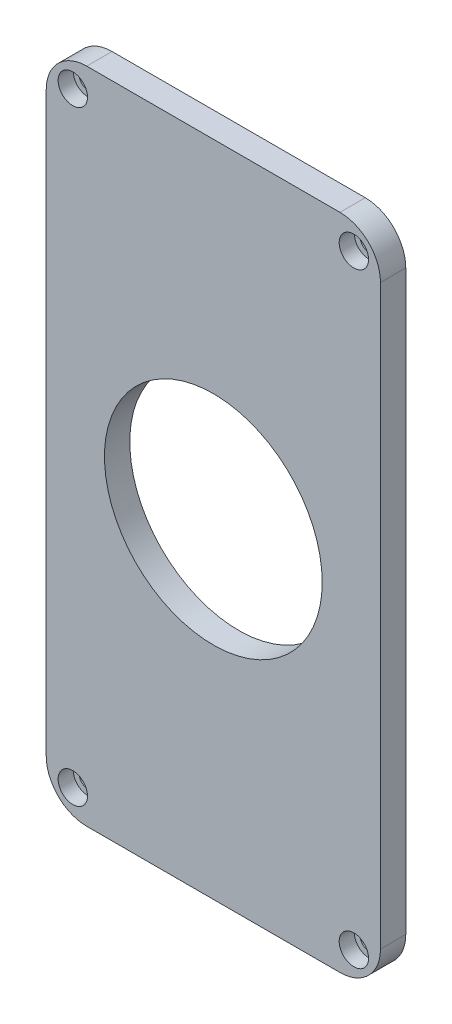
SolidWorks part; units mm, degrees
ref_plane "Front Plane" through (0, 0, 0) normal (0, 0, 1) x (1, 0, 0)
ref_plane "Top Plane" through (0, 0, 0) normal (0, 1, 0) x (1, 0, 0)
ref_plane "Right Plane" through (0, 0, 0) normal (1, 0, 0) x (0, 0, -1)
sketch "Sketch1" plane through (0, 0, 0) normal (0, 0, 1) x (1, 0, 0)
  line L5 (25, 65) -> (-25, 65)
  line L6 (33, 57) -> (33, -57)
  line L7 (25, -65) -> (-25, -65)
  line L8 (-33, 57) -> (-33, -57)
  line L9 (33, 65) -> (-33, -65) construction
  line L10 (33, -65) -> (-33, 65) construction
  arc A4 (-33, -57) -> (-25, -65) centre (-25, -57) ccw
  arc A5 (25, -65) -> (33, -57) centre (25, -57) ccw
  arc A6 (33, 57) -> (25, 65) centre (25, 57) ccw
  arc A7 (-33, 57) -> (-25, 65) centre (-25, 57) cw
  point P0 (0, 0)
  dimension "D1" = 130
  dimension "D2" = 8
  dimension "D3" = 50
extrude "Boss-Extrude1" add sketch "Sketch1" along normal blind 5
sketch "Sketch2" plane through (0, 0, 5) normal (0, 0, 1) x (1, 0, 0)
  circle A0 centre (0, 0) radius 21.5
  dimension "D1" = 43
extrude "Cut-Extrude1" cut sketch "Sketch2" against normal through all
sketch "Sketch12" plane through (0, 0, 5) normal (0, 0, 1) x (1, 0, 0)
  line L6 (0, 0) -> (0, 59.75) construction
  line L7 (0, 59.75) -> (-27.75, 59.75) construction
  line L8 (0, 0) -> (-27.75, 0) construction
  line L9 (-27.75, 0) -> (-27.75, 59.75) construction
  line L10 (-27.75, 59.75) -> (-30.6569, 59.446) construction
  circle A0 centre (-27.75, 59.75) radius 2.9
  circle A1 centre (27.75, 59.75) radius 2.9
  circle A2 centre (-27.75, -59.75) radius 2.9
  circle A3 centre (27.75, -59.75) radius 2.9
  circle A4 centre (-27.75, 59.75) radius 3 construction
  dimension "D3" = 5.8
  dimension "D4" = 6
  dimension "D1" = 27.75
  dimension "D2" = 59.75
extrude "Cut-Extrude3" cut sketch "Sketch12" against normal blind 3
sketch "Sketch13" plane through (0, 0, 2) normal (0, 0, 1) x (1, 0, 0)
  line L0 (0, 0) -> (0, 65) construction
  line L1 (25, 65) -> (-25, 65) construction
  line L2 (0, 0) -> (-27.75, 0) construction
  circle A0 centre (-27.75, 59.75) radius 1.75
  circle A1 centre (27.75, 59.75) radius 1.75
  circle A2 centre (27.75, -59.75) radius 1.75
  circle A3 centre (-27.75, -59.75) radius 1.75
  dimension "D1" = 3.5
extrude "Cut-Extrude4" cut sketch "Sketch13" against normal through all
